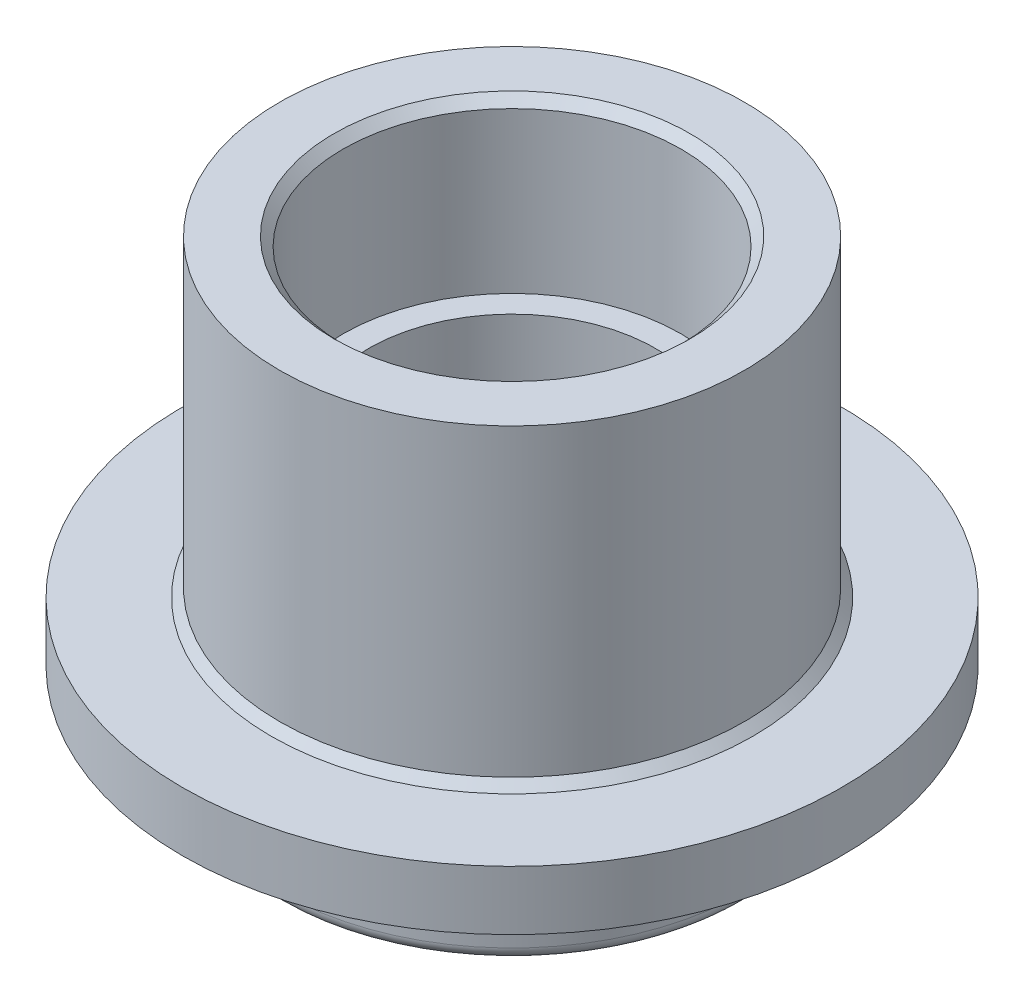
SolidWorks part; units mm, degrees
material "Alliage 1060"
ref_plane "Plan de face" through (0, 0, 0) normal (0, 0, 1) x (1, 0, 0)
ref_plane "Plan de dessus" through (0, 0, 0) normal (0, 1, 0) x (1, 0, 0)
ref_plane "Plan de droite" through (0, 0, 0) normal (1, 0, 0) x (0, 0, -1)
sketch "Esquisse1" plane through (0, 0, 0) normal (0, 0, 1) x (1, 0, 0)
  line L0 (0, 425.2439) -> (0, -360.8537) construction
  line L1 (0, -180) -> (260, -180)
  line L2 (275, -165) -> (275, -70)
  line L3 (275, -70) -> (390, -70)
  line L4 (390, -70) -> (390, 0)
  line L5 (390, 0) -> (285, 0)
  line L6 (275, 10) -> (275, 370)
  line L7 (275, 370) -> (0, 370)
  line L8 (0, 370) -> (0, -180)
  line L9 (200, -180) -> (200, -60)
  line L10 (200, -60) -> (170, -60)
  line L11 (170, -60) -> (170, 170)
  line L12 (200, 170) -> (170, 170)
  line L13 (200, 170) -> (200, 359.3934)
  line L14 (200, 359.3934) -> (210.6066, 370)
  line L15 (210.6066, 370) -> (0, 370)
  line L16 (0, -180) -> (200, -180)
  line L17 (285, 0) -> (275, 10)
  arc A0 (260, -180) -> (275, -165) centre (260, -165) ccw
  point P9 (275, 0)
  point P13 (185, -60)
  dimension "D14" = 15
  dimension "D1" = 110
  dimension "D2" = 70
  dimension "D3" = 550
  dimension "D4" = 275
  dimension "D5" = 390
  dimension "D6" = 275
  dimension "D7" = 200
  dimension "D8" = 170
  dimension "D9" = 200
  dimension "D10" = 225
  dimension "D11" = 15
  dimension "D12" = 120
  dimension "D13" = 230
revolve "Révolution1" add sketch "Esquisse1" angle 360 about L0
